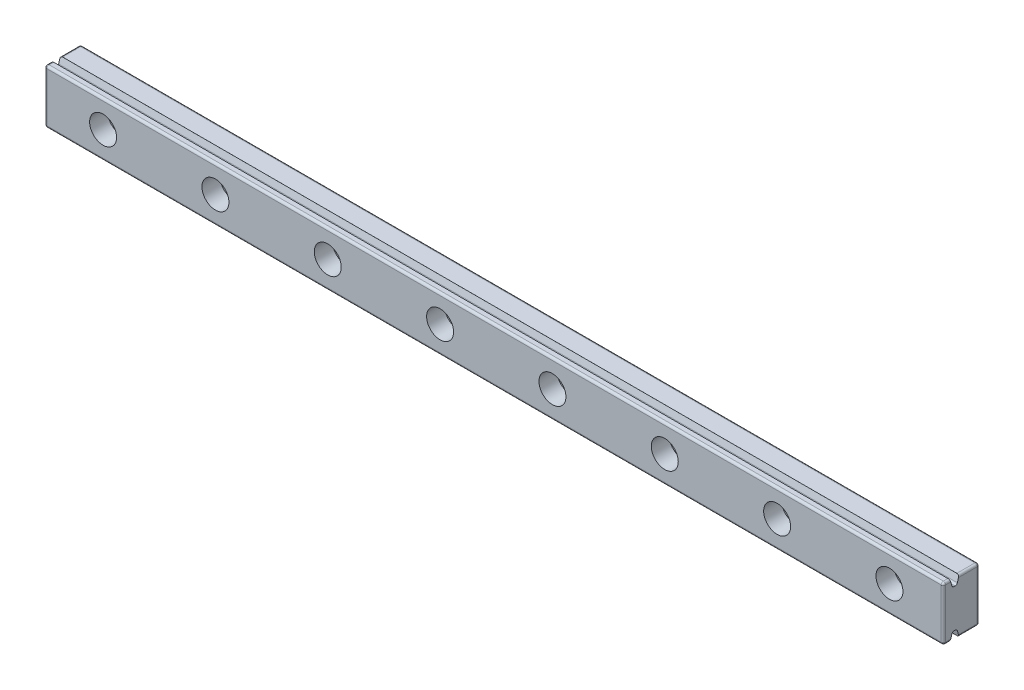
SolidWorks part; units mm, degrees
ref_plane "Front Plane" through (0, 0, 0) normal (0, 0, 1) x (1, 0, 0)
ref_plane "Top Plane" through (0, 0, 0) normal (0, 1, 0) x (1, 0, 0)
ref_plane "Right Plane" through (0, 0, 0) normal (1, 0, 0) x (0, 0, -1)
sketch "Sketch1" plane through (0, 0, 0) normal (1, 0, 0) x (0, 0, -1)
  line L0 (-0.5, 6) -> (4, 6)
  line L1 (-4, 6) -> (-2.5, 6)
  line L2 (-4, 6) -> (-4, -6)
  line L3 (-4, -6) -> (-2.5, -6)
  line L4 (4, 6) -> (4, -6)
  line L5 (-4, 6) -> (4, -6) construction
  line L6 (-4, -6) -> (4, 6) construction
  line L8 (-2.5, 6) -> (-2.5, 4.25)
  line L9 (-2.5, 4.25) -> (-0.5, 4.25)
  line L10 (-0.5, 6) -> (-0.5, 4.25)
  line L12 (-2.5, -6) -> (-2.5, -4.25)
  line L13 (-2.5, -4.25) -> (-0.5, -4.25)
  line L14 (-0.5, -6) -> (-0.5, -4.25)
  line L15 (-0.5, -6) -> (4, -6)
  point P0 (0, 0)
  dimension "D1" = 12
  dimension "D2" = 8
  dimension "D3" = 2
  dimension "D4" = 2
  dimension "D5" = 1.5
  dimension "D6" = 1.5
  dimension "D7" = 8.5
  dimension "D8" = 4.25
extrude "Boss-Extrude1" add sketch "Sketch1" along normal blind 200
sketch "Sketch2" plane through (0, 0, 4) normal (0, 0, 1) x (1, 0, 0)
  line L0 (0, 6) -> (0, -6) construction
  circle A0 centre (13, 0) radius 1.75
  circle A1 centre (38, 0) radius 1.75
  circle A2 centre (63, 0) radius 1.75
  circle A3 centre (88, 0) radius 1.75
  circle A4 centre (113, 0) radius 1.75
  circle A5 centre (138, 0) radius 1.75
  circle A6 centre (163, 0) radius 1.75
  circle A7 centre (188, 0) radius 1.75
  circle A8 centre (213, 0) radius 1.75
  circle A9 centre (238, 0) radius 1.75
  circle A10 centre (263, 0) radius 1.75
  circle A11 centre (288, 0) radius 1.75
  circle A12 centre (313, 0) radius 1.75
  circle A13 centre (338, 0) radius 1.75
  circle A14 centre (363, 0) radius 1.75
  circle A15 centre (388, 0) radius 1.75
  dimension "D1" = 3.5
  dimension "D2" = 13
  dimension "D3" = 16
extrude "Cut-Extrude1" cut sketch "Sketch2" against normal blind 10
sketch "Sketch3" plane through (0, 0, 4) normal (0, 0, 1) x (1, 0, 0)
  circle A0 centre (13, 0) radius 3
  circle A1 centre (38, 0) radius 3
  circle A2 centre (63, 0) radius 3
  circle A3 centre (88, 0) radius 3
  circle A4 centre (113, 0) radius 3
  circle A5 centre (138, 0) radius 3
  circle A6 centre (163, 0) radius 3
  circle A7 centre (188, 0) radius 3
  circle A8 centre (213, 0) radius 3
  circle A9 centre (238, 0) radius 3
  circle A10 centre (263, 0) radius 3
  circle A11 centre (288, 0) radius 3
  circle A12 centre (313, 0) radius 3
  circle A13 centre (338, 0) radius 3
  circle A14 centre (363, 0) radius 3
  circle A15 centre (388, 0) radius 3
  dimension "D1" = 6
  dimension "D2" = 16
extrude "Cut-Extrude2" cut sketch "Sketch3" against normal blind 4
chamfer "Chamfer1" distance 0.5 angle 74 4 edges at (100, -4.25, 2.5) (100, -4.25, 0.5) (100, 4.25, 2.5) (100, 4.25, 0.5)
fillet "Fillet1" radius 0.5 20 edges at (200, -6, -1.75) (200, 0, -4) (200, 6, -1.75) (200, 6, 3.25) (200, 0, 4) (200, -6, 3.25) (0, -6, 3.25) (0, -6, -1.75) (0, 0, -4) (0, 6, -1.75) (0, 6, 3.25) (0, 0, 4) (100, -4.25, 1) (100, -4.25, 2) (100, 4.25, 2) (100, 4.25, 1) (100, -6, 4) (100, 6, 4) (100, -6, -4) (100, 6, -4)
